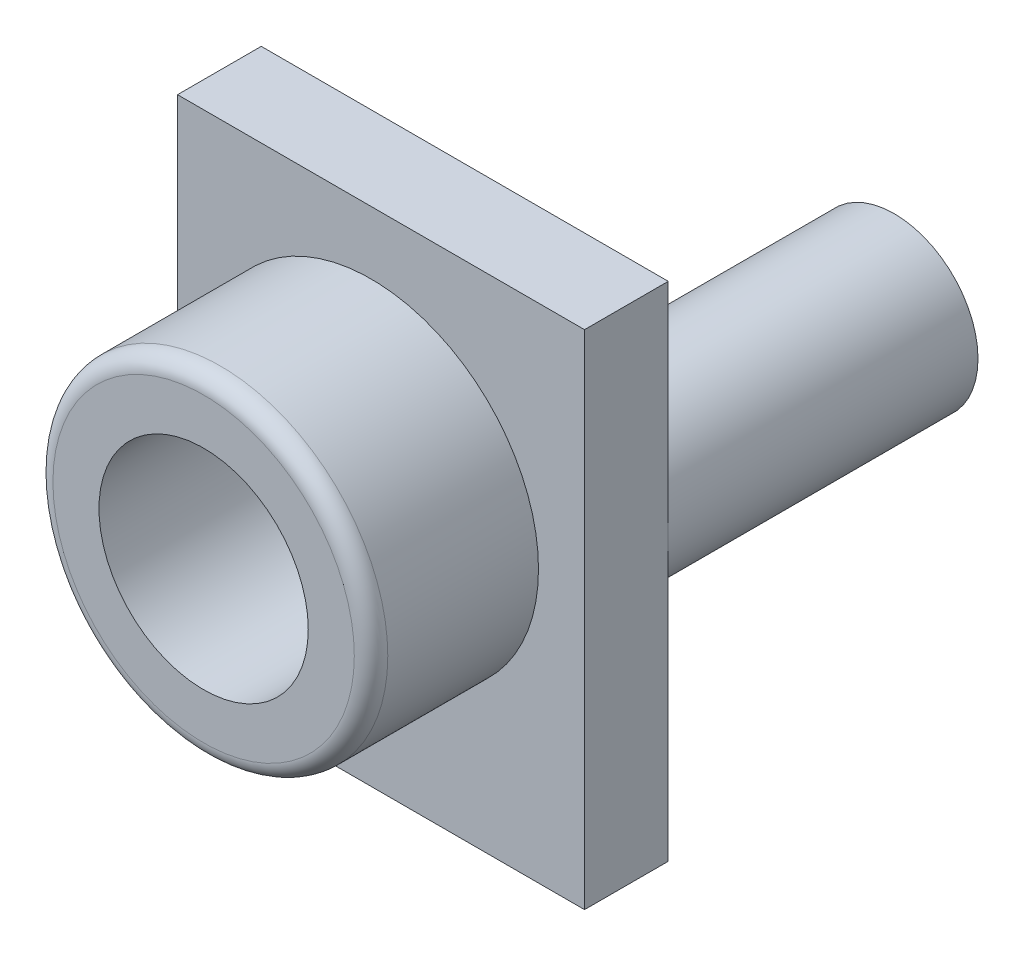
SolidWorks part; units mm, degrees
ref_plane "Спереди" through (0, 0, 0) normal (0, 0, 1) x (1, 0, 0)
ref_plane "Сверху" through (0, 0, 0) normal (0, 1, 0) x (1, 0, 0)
ref_plane "Справа" through (0, 0, 0) normal (1, 0, 0) x (0, 0, -1)
other "Configuration Table"
sketch "Эскиз1" plane through (0, 0, 0) normal (0, 0, 1) x (1, 0, 0)
  line L0 (4.8616, -6) -> (4.8616, 6)
  line L1 (4.8616, 6) -> (-4.8616, 6)
  line L2 (-4.8616, 6) -> (-4.8616, -6)
  line L3 (-4.8616, -6) -> (4.8616, -6)
  circle A0 centre (-0.2384, 0.5) radius 4
  circle A1 centre (-0.2384, 0.5) radius 2.5
  circle A2 centre (2.8616, 0.7) radius 2
sketch "Эскиз2" plane through (0, 0, 0) normal (0, 0, 1) x (1, 0, 0)
  line L0 (-4.8616, -6) -> (4.8616, -6) construction
  line L1 (4.8616, -6) -> (4.8616, 6) construction
  line L2 (4.8616, 6) -> (-4.8616, 6) construction
  line L3 (-4.8616, 6) -> (-4.8616, -6) construction
  line L4 (-4.8616, -6) -> (4.8616, -6)
  line L5 (4.8616, -6) -> (4.8616, 6)
  line L6 (4.8616, 6) -> (-4.8616, 6)
  line L7 (-4.8616, 6) -> (-4.8616, -6)
extrude "Бобышка-Вытянуть1" add sketch "Эскиз2" along normal blind 2
sketch "Эскиз3" plane through (0, 0, 2) normal (0, 0, 1) x (1, 0, 0)
  circle A0 centre (-0.2384, 0.5) radius 2.5 construction
  circle A1 centre (-0.2384, 0.5) radius 4 construction
  circle A2 centre (-0.2384, 0.5) radius 2.5
  circle A3 centre (-0.2384, 0.5) radius 4
extrude "Бобышка-Вытянуть2" add sketch "Эскиз3" along normal blind 4
sketch "Эскиз4" plane through (0, 0, 0) normal (0, 0, -1) x (-1, 0, 0)
  circle A0 centre (-2.8616, 0.7) radius 2 construction
  circle A1 centre (-2.8616, 0.7) radius 2
extrude "Бобышка-Вытянуть3" add sketch "Эскиз4" along normal blind 7.4
fillet "Скругление1" radius 0.4 1 edges at (3.7616, 0.5, 6)
sketch "hole" plane through (0, 0, 6) normal (0, 0, 1) x (1, 0, 0)
  circle A0 centre (-0.2384, 0.5) radius 2.5 construction
  circle A1 centre (-0.2384, 0.5) radius 2.5
